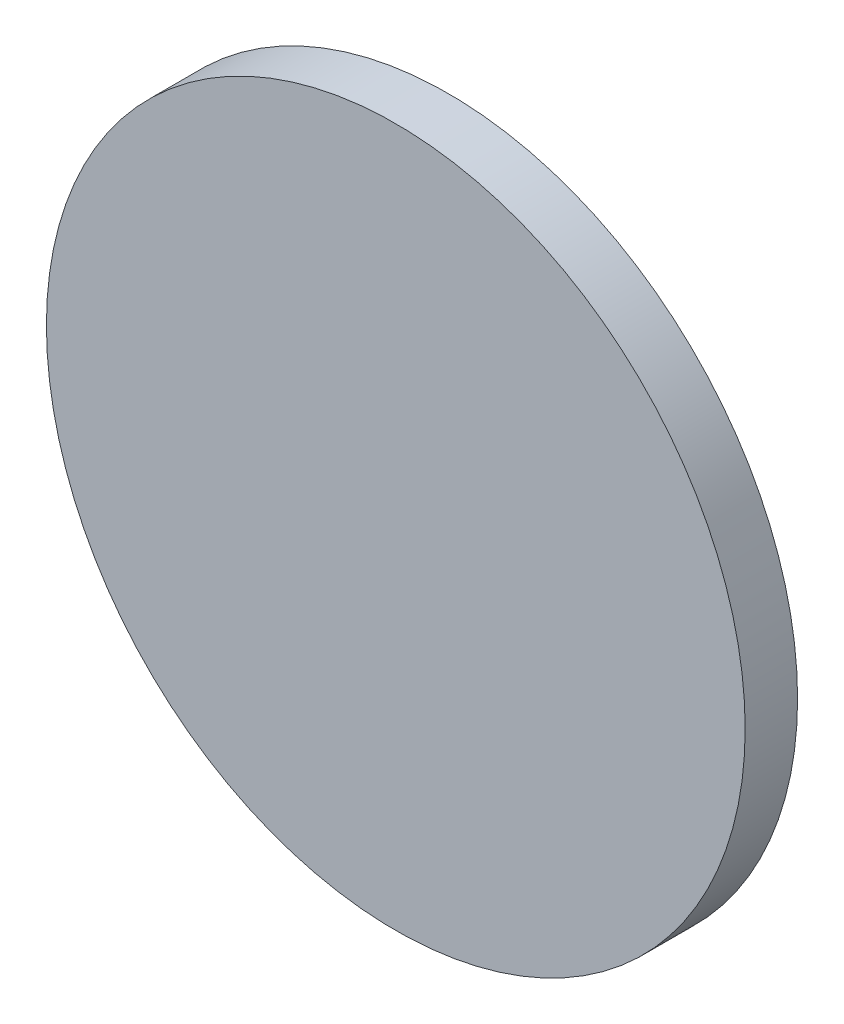
SolidWorks part; units mm, degrees
ref_plane "前视" through (0, 0, 0) normal (0, 0, 1) x (1, 0, 0)
ref_plane "上视" through (0, 0, 0) normal (0, 1, 0) x (1, 0, 0)
ref_plane "右视" through (0, 0, 0) normal (1, 0, 0) x (0, 0, -1)
sketch "草图1" plane through (0, 0, 0) normal (0, 0, 1) x (1, 0, 0)
  circle A0 centre (0, 0) radius 40
  dimension "D1" = 80
extrude "凸台-拉伸1" add sketch "草图1" along normal blind 6 contours A0
